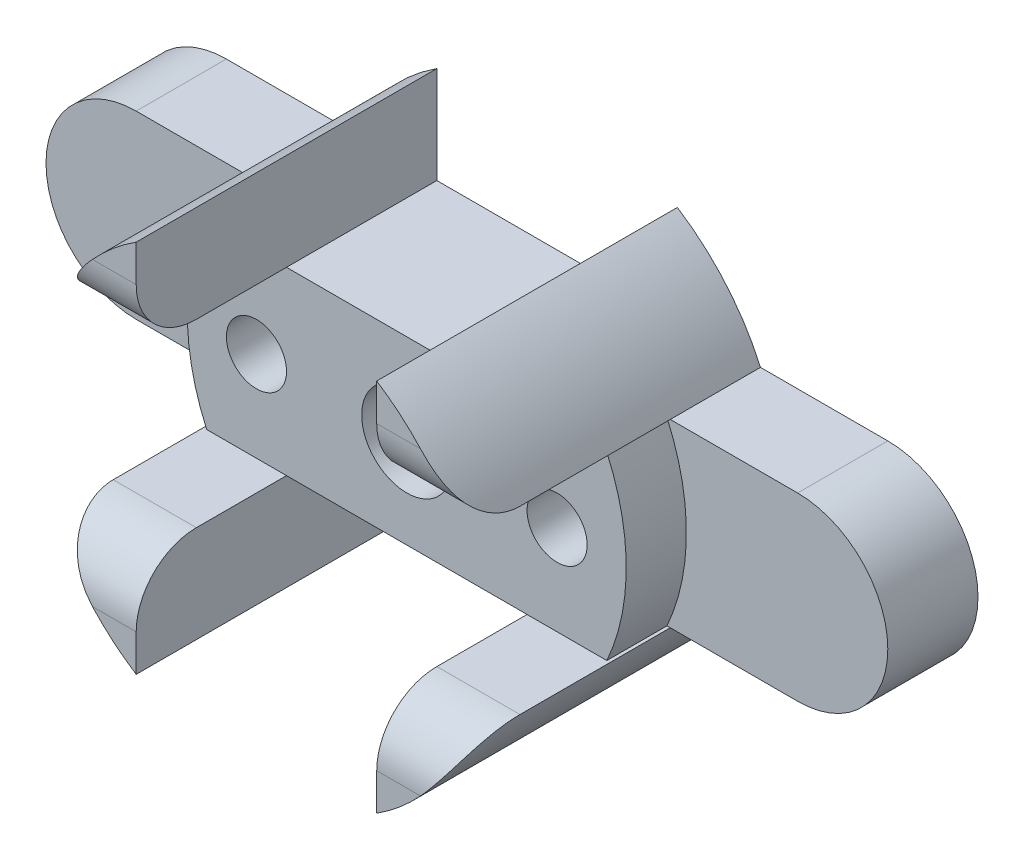
SolidWorks part; units mm, degrees
ref_plane "前视基准面" through (0, 0, 0) normal (0, 0, 1) x (1, 0, 0)
ref_plane "上视基准面" through (0, 0, 0) normal (0, 1, 0) x (1, 0, 0)
ref_plane "右视基准面" through (0, 0, 0) normal (1, 0, 0) x (0, 0, -1)
sketch "草图1" plane through (0, 0, 0) normal (0, 1, 0) x (1, 0, 0)
  line L0 (0, 0) -> (0, -16.0369) construction
  line L5 (0, 0) -> (0, 5)
  line L6 (0, 5) -> (20, 5)
  line L7 (20, 5) -> (20, 2)
  line L8 (20, 2) -> (7.3, 2)
  line L9 (7.3, 2) -> (7.3, 0)
  line L10 (7.3, 0) -> (0, 0)
  dimension "D1" = 7.3
  dimension "D2" = 20
  dimension "D3" = 3
  dimension "D4" = 2
revolve "旋转3" add sketch "草图1" angle 360 about L0
sketch "草图2" plane through (0, 0, 0) normal (0, 0, 1) x (1, 0, 0)
  line L0 (11, 0) -> (-11, 0) construction
  line L1 (-24.8312, -21.974) -> (24.8312, -21.974)
  line L2 (-24.8312, -21.974) -> (-24.8312, 21.974)
  line L3 (-24.8312, 21.974) -> (24.8312, 21.974)
  line L4 (24.8312, -21.974) -> (24.8312, 21.974)
  line L5 (-24.8312, -21.974) -> (24.8312, 21.974) construction
  line L6 (-24.8312, 21.974) -> (24.8312, -21.974) construction
  line L11 (11, -3) -> (-11, -3)
  line L12 (11, 3) -> (-11, 3)
  arc A0 (11, -3) -> (11, 3) centre (11, 0) ccw
  arc A1 (-11, 3) -> (-11, -3) centre (-11, 0) ccw
  point P7 (0, 0)
  point P13 (0, 0)
  circle M3 centre (0, 0) radius 7.3
  dimension "D1" = 3
  dimension "D2" = 22
extrude "切除-拉伸1" cut sketch "草图2" against normal blind 10 contours L1 L4 L3 L2 A1 L12 A0 L11 M3 | L12 M3 | L11 M3
sketch "草图3" plane through (0, 0, 0) normal (0, 0, 1) x (1, 0, 0)
  circle A0 centre (0, 0) radius 1.5
  circle A1 centre (5, 0) radius 1
  circle A2 centre (-5, 0) radius 1
  dimension "D1" = 3
  dimension "D2" = 2
  dimension "D3" = 2
  dimension "D4" = 10
  dimension "D5" = 5
extrude "切除-拉伸2" cut sketch "草图3" against normal through all
sketch "草图4" plane through (0, 0, -5) normal (0, 0, -1) x (-1, 0, 0)
  line L0 (-4, 6.2258) -> (-4, -6.2258)
  line L1 (4, 6.2258) -> (4, -6.2258)
  circle A0 centre (0, 0) radius 7.4
  line M8 (11, 3) -> (-11, 3)
  line M10 (-11, -3) -> (11, -3)
  dimension "D1" = 14.8
  dimension "D2" = 8
extrude "凸台-拉伸1" add sketch "草图4" against normal blind 10 contours L0 A0 M8 | A0 L1 M8 | L1 A0 M10 | A0 L0 M10
fillet "圆角1" radius 2 4 edges at (-5.3823, -3, 5) (5.3823, -3, 5) (5.3823, 3, 5) (-5.3823, 3, 5)
